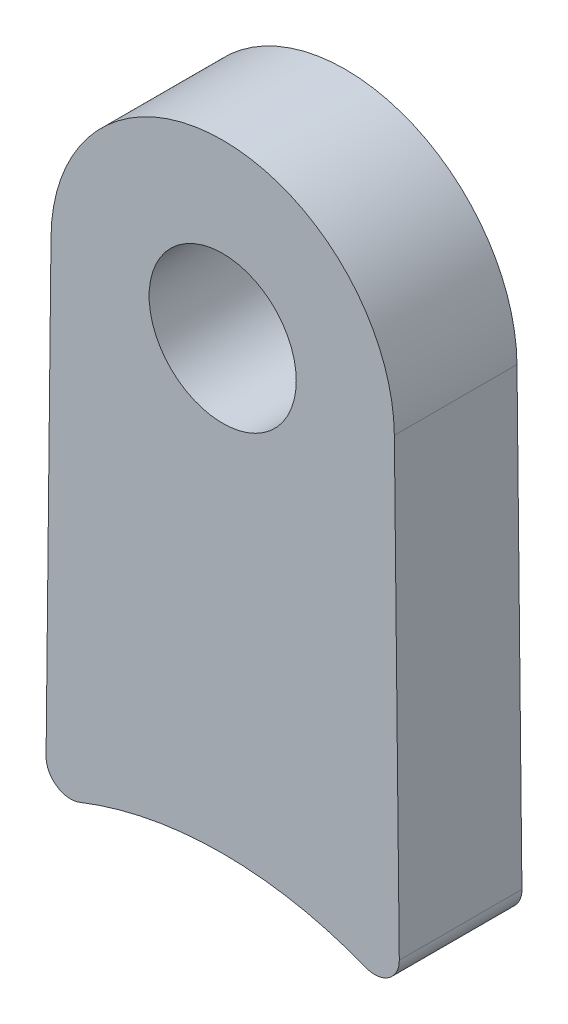
SolidWorks part; units mm, degrees
ref_plane "Front Plane" through (0, 0, 0) normal (0, 0, 1) x (1, 0, 0)
ref_plane "Top Plane" through (0, 0, 0) normal (0, 1, 0) x (1, 0, 0)
ref_plane "Right Plane" through (0, 0, 0) normal (1, 0, 0) x (0, 0, -1)
sketch "Sketch1" plane through (0, 0, 0) normal (0, 0, 1) x (1, 0, 0)
  line L0 (-7.2178, 14.1393) -> (-6.9996, 34.1381)
  line L1 (7.2178, 14.1393) -> (6.9996, 34.1381)
  arc A0 (-7.2178, 14.1393) -> (7.2178, 14.1393) centre (0, 0) cw
  arc A1 (-6.9996, 34.1381) -> (6.9996, 34.1381) centre (0, 34.0617) cw
  circle A2 centre (0, 34.0617) radius 3
  dimension "D1" = 15.875
  dimension "D2" = 6
  dimension "D3" = 4
  dimension "D4" = 34.0617
  dimension "D5" = 20
extrude "Boss-Extrude1" add sketch "Sketch1" along normal blind 5
fillet "Fillet1" radius 1 2 edges at (7.2178, 14.1393, 2.5) (-7.2178, 14.1393, 2.5)
